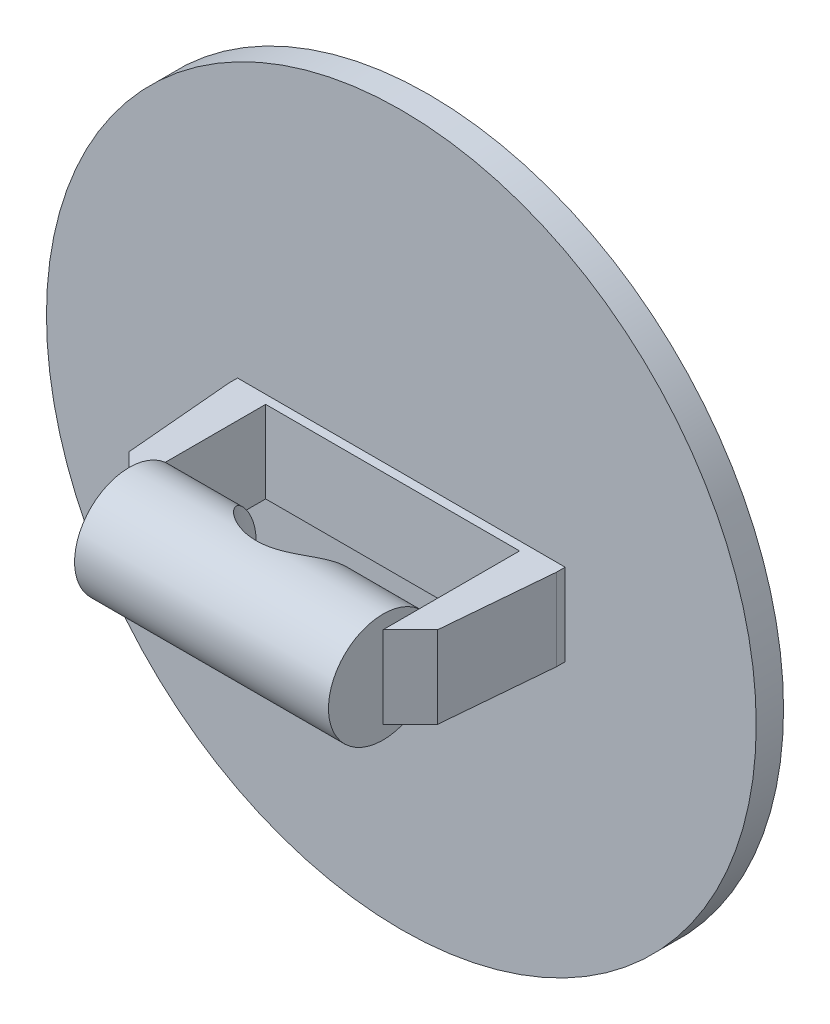
SolidWorks part; units mm, degrees
material "ABS"
ref_plane "Front Plane" through (0, 0, 0) normal (0, 0, 1) x (1, 0, 0)
ref_plane "Top Plane" through (0, 0, 0) normal (0, 1, 0) x (1, 0, 0)
ref_plane "Right Plane" through (0, 0, 0) normal (1, 0, 0) x (0, 0, -1)
sketch "Sketch1" plane through (0, 0, 0) normal (0, 0, 1) x (1, 0, 0)
  circle A0 centre (0, 0) radius 10.3187
  point P2 (0, 0)
  dimension "D1" = 20.6375
extrude "Boss-Extrude1" add sketch "Sketch1" against normal blind 0.7937
ref_plane "Plane1" through (0, 0, -2.3812) normal (0, 0, -1) x (-1, 0, 0)
sketch "Sketch3" plane through (0, 0, -2.3812) normal (0, 0, -1) x (-1, 0, 0)
  point P0 (0, 0)
sketch "Sketch4" plane through (0, 0, 0) normal (1, 0, 0) x (0, 0, -1)
  line L0 (0.7937, 0) -> (0.7937, 10.3187)
  line L1 (0.7937, -10.3187) -> (0.7937, 10.3187) construction
  line L2 (0.7937, 0) -> (2.3812, 0)
  arc A0 (2.3812, 0) -> (0.7937, 10.3187) centre (-31.9484, 0) ccw
revolve "Revolve1" add sketch "Sketch4" angle 360 about L2
sketch "Sketch5" plane through (0, 0, 0) normal (0, 0, 1) x (1, 0, 0)
  line L0 (-4.7625, 1.1906) -> (4.7625, -1.1906) construction
  line L1 (-4.7625, 1.1906) -> (4.7625, 1.1906)
  line L2 (-4.7625, 1.1906) -> (-4.7625, -1.1906)
  line L3 (-4.7625, -1.1906) -> (4.7625, -1.1906)
  line L4 (4.7625, 1.1906) -> (4.7625, -1.1906)
  dimension "D1" = 9.525
  dimension "D2" = 2.3813
extrude "Boss-Extrude2" add sketch "Sketch5" along normal blind 0.254
sketch "Sketch6" plane through (0, -1.1906, 0) normal (0, -1, 0) x (1, 0, 0)
  line L0 (-4.7625, 0.254) -> (-3.691, 0.254)
  line L1 (-4.7625, 0.254) -> (4.7625, 0.254) construction
  line L2 (-3.691, 0.254) -> (-3.691, 4.2227)
  line L3 (-3.691, 4.2227) -> (-4.4847, 3.429)
  line L4 (-4.4847, 3.429) -> (-4.7625, 0.254)
  line L5 (-4.7625, 0.254) -> (-4.7625, 0) construction
  line L6 (0, 0) -> (0, 4.2227) construction
  line L7 (4.7625, 0.254) -> (3.691, 0.254)
  line L8 (4.4847, 3.429) -> (4.7625, 0.254)
  line L9 (3.691, 4.2227) -> (4.4847, 3.429)
  line L10 (3.691, 0.254) -> (3.691, 4.2227)
  dimension "D1" = 3.175
  dimension "D2" = 3.9688
  dimension "D3" = 135
  dimension "D4" = 5
extrude "Boss-Extrude3" add sketch "Sketch6" against normal blind 2.3813
sketch "Sketch7" plane through (-3.691, 0, 0) normal (1, 0, 0) x (0, 0, -1)
  line L0 (0, 0) -> (-4.2227, 0) construction
  line L1 (-4.2227, 1.1906) -> (-4.2227, -1.1906) construction
  circle A0 centre (-4.2227, 0) radius 1.5875
  dimension "D1" = 3.175
extrude "Boss-Extrude4" add sketch "Sketch7" along normal up to surface (7.3819 mm away) up to face at (3.691, 0, 2.2384)
sketch "Sketch8" plane through (0, -1.1906, 0) normal (0, -1, 0) x (1, 0, 0)
  line L0 (-3.691, 4.2227) -> (3.691, 4.2227) construction
  line L1 (0, 0) -> (0, 4.2227) construction
  line L2 (-3.691, 2.6353) -> (3.691, 2.6353) construction
  line L8 (-3.691, 0.254) -> (-3.691, 3.1727) construction
  line L9 (3.691, 3.1727) -> (3.691, 0.254) construction
  circle A0 centre (0, 2.6353) radius 1.5875
  point P9 (0, 2.6353)
  dimension "D2" = 3.175
  dimension "D1" = 1.5875
extrude "Cut-Extrude1" cut sketch "Sketch8" against normal through all and the other way through all
